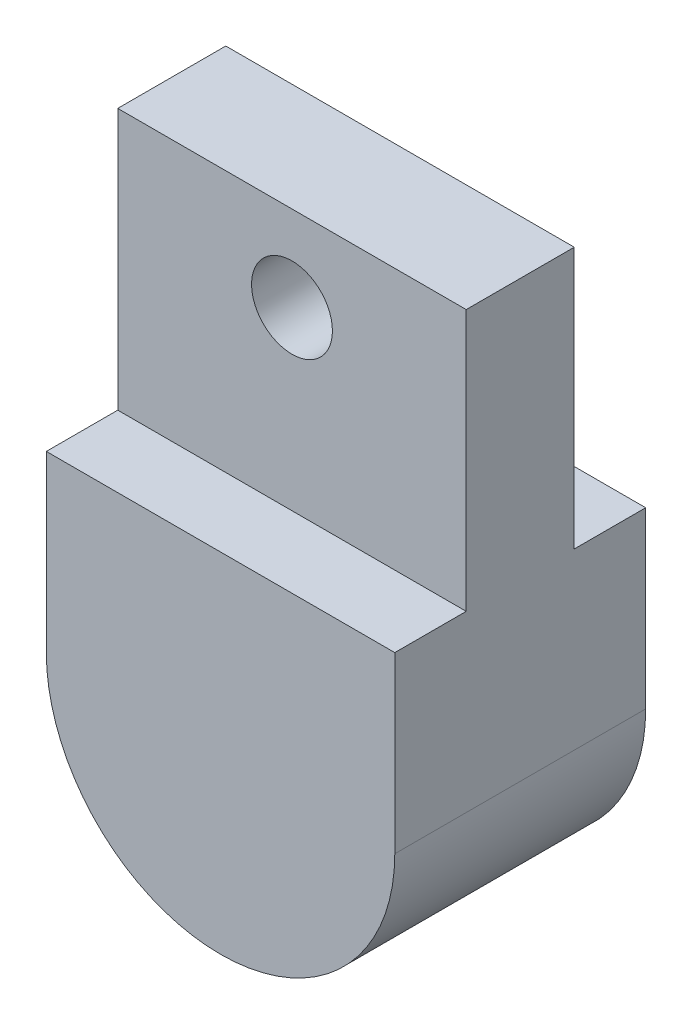
SolidWorks part; units mm, degrees
ref_plane "Front Plane" through (0, 0, 0) normal (0, 0, 1) x (1, 0, 0)
ref_plane "Top Plane" through (0, 0, 0) normal (0, 1, 0) x (1, 0, 0)
ref_plane "Right Plane" through (0, 0, 0) normal (1, 0, 0) x (0, 0, -1)
sketch "Sketch1" plane through (0, 0, 0) normal (0, 1, 0) x (1, 0, 0)
  line L1 (-6.35, 1.9685) -> (6.35, 1.9685)
  line L2 (-6.35, 1.9685) -> (-6.35, -1.9685)
  line L3 (-6.35, -1.9685) -> (6.35, -1.9685)
  line L4 (6.35, 1.9685) -> (6.35, -1.9685)
  line L5 (-6.35, 1.9685) -> (6.35, -1.9685) construction
  line L6 (-6.35, -1.9685) -> (6.35, 1.9685) construction
  point P0 (0, 0)
  dimension "D1" = 3.937
  dimension "D2" = 12.7
extrude "Boss-Extrude1" add sketch "Sketch1" against normal blind 9.525
hole_wizard "#4 Clearance Hole1" positions "Sketch5" profile "Sketch6" hole size "#4" standard "ANSI Inch" end condition through all
sketch "Sketch5" plane through (0, 0, 1.9685) normal (0, 0, 1) x (1, 0, 0)
  point P0 (0, -3.1115)
sketch "Sketch6" plane through (0, -3.1115, 1.9685) normal (1, 0, 0) x (0, -1, 0)
  line L0 (0, 0) -> (0, 3.937)
  line L1 (0, 3.937) -> (1.4732, 3.937)
  line L2 (1.4732, 3.937) -> (1.4732, 0)
  line L5 (1.4732, 0) -> (0, 0)
  line L11 (0, -6.35) -> (0, 107.95) construction
  dimension "Thru Hole Dia." = 2.9464
  dimension "Thru Hole Depth" = 3.937
sketch "Sketch4" plane through (0, 0, 1.9685) normal (0, 0, 1) x (1, 0, 0)
  line L0 (0, -3.1115) -> (0, 0) construction
  circle A0 centre (0, -3.1115) radius 1.4732
  dimension "D2" = 2.9464
  dimension "D1" = 3.1115
ref_plane "Plane1" through (0, 0, 4.572) normal (0, 0, 1) x (1, 0, 0)
sketch "Sketch8" plane through (-1.778, 0, 4.572) normal (0, 0, -1) x (-1, 0, 0)
  line L2 (4.572, -15.875) -> (4.572, -9.525)
  line L3 (4.572, -9.525) -> (-8.128, -9.525)
  line L4 (-8.128, -15.875) -> (-8.128, -9.525)
  line L5 (4.572, -9.525) -> (-8.128, -9.525) construction
  arc A0 (-8.128, -15.875) -> (4.572, -15.875) centre (-1.778, -15.875) ccw
  point P5 (-1.778, -9.525)
  point P10 (-1.778, -22.225)
  point P13 (-1.778, -9.525)
  dimension "D2" = 12.7
extrude "Boss-Extrude3" add sketch "Sketch8" along normal blind 9.144
